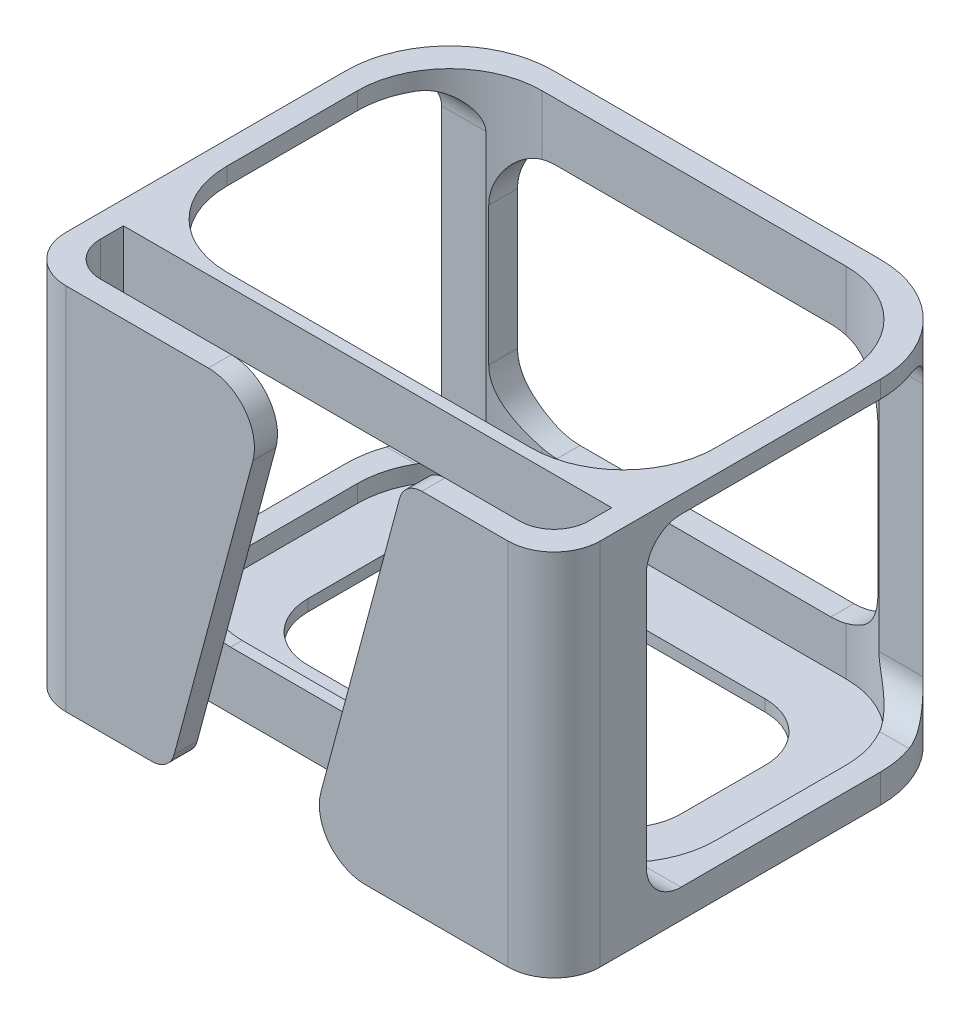
SolidWorks part; units mm, degrees
ref_plane "Front Plane" through (0, 0, 0) normal (0, 0, 1) x (1, 0, 0)
ref_plane "Top Plane" through (0, 0, 0) normal (0, 1, 0) x (1, 0, 0)
ref_plane "Right Plane" through (0, 0, 0) normal (1, 0, 0) x (0, 0, -1)
sketch "Sketch1" plane through (0, 0, 0) normal (0, 1, 0) x (1, 0, 0)
  line L0 (-0.3998, -21.65) -> (18.175, -21.65)
  line L1 (-14.175, 13.65) -> (12.175, 13.65)
  line L2 (-22.175, 5.65) -> (-22.175, -5.65)
  line L3 (-14.175, -13.65) -> (12.175, -13.65)
  line L4 (20.175, 5.65) -> (20.175, -5.65)
  line L5 (-22.175, -14.65) -> (20.175, -14.65)
  line L6 (-22.175, -14.65) -> (-22.175, -16.65)
  line L7 (-15.175, 15.65) -> (13.175, 15.65)
  line L8 (-24.175, 6.65) -> (-24.175, -8.65)
  line L10 (22.175, 6.65) -> (22.175, -8.65)
  line L11 (-19.175, -19.65) -> (-1.7581, -19.65)
  line L12 (20.175, -14.65) -> (20.175, -16.65)
  line L14 (-24.175, -8.65) -> (-24.175, -17.65)
  line L15 (-20.175, -21.65) -> (-1.7581, -21.65)
  line L16 (22.175, -8.65) -> (22.175, -17.65)
  line L18 (-1.7581, -21.65) -> (-1.7581, -19.65)
  line L20 (-0.3998, -21.65) -> (-0.3998, -19.65)
  line L23 (-0.3998, -19.65) -> (17.175, -19.65)
  arc A0 (12.175, 13.65) -> (20.175, 5.65) centre (12.175, 5.65) cw
  arc A1 (-22.175, -5.65) -> (-14.175, -13.65) centre (-14.175, -5.65) ccw
  arc A2 (-14.175, 13.65) -> (-22.175, 5.65) centre (-14.175, 5.65) ccw
  arc A3 (12.175, -13.65) -> (20.175, -5.65) centre (12.175, -5.65) ccw
  arc A6 (13.175, 15.65) -> (22.175, 6.65) centre (13.175, 6.65) cw
  arc A7 (-15.175, 15.65) -> (-24.175, 6.65) centre (-15.175, 6.65) ccw
  arc A8 (18.175, -21.65) -> (22.175, -17.65) centre (18.175, -17.65) ccw
  arc A9 (-24.175, -17.65) -> (-20.175, -21.65) centre (-20.175, -17.65) ccw
  arc A10 (17.175, -19.65) -> (20.175, -16.65) centre (17.175, -16.65) ccw
  arc A11 (-22.175, -16.65) -> (-19.175, -19.65) centre (-19.175, -16.65) ccw
  point P0 (0, 0)
  point P18 (0, 0)
  point P37 (-1, -21.65)
  dimension "D3" = 8
  dimension "D6" = 4
  dimension "D4" = 2
  dimension "D11" = 3
  dimension "D2" = 2
  dimension "D5" = 2
  dimension "D7" = 1
  dimension "D8" = 2
  dimension "D9" = 2
  dimension "D10" = 2
extrude "Boss-Extrude5" add sketch "Sketch1" along normal blind 32 contours A7 L8 L14 A9 L15 L18 L11 A11 L6 L5 L12 A10 L23 L20 L0 A8 L16 L10 A6 L7
sketch "Sketch6" plane through (0, 32, 0) normal (0, 1, 0) x (1, 0, 0)
  line L0 (-14.175, 13.65) -> (12.175, 13.65)
  line L1 (-22.175, 5.65) -> (-22.175, -5.65)
  line L2 (-14.175, -13.65) -> (12.175, -13.65)
  line L3 (20.175, 5.65) -> (20.175, -5.65)
  line L4 (-15.175, 15.65) -> (13.175, 15.65) construction
  line L5 (-24.175, 6.65) -> (-24.175, -17.65) construction
  line L6 (22.175, 6.65) -> (22.175, -17.65) construction
  line L7 (-22.175, -14.65) -> (20.175, -14.65) construction
  arc A0 (12.175, 13.65) -> (20.175, 5.65) centre (12.175, 5.65) cw
  arc A1 (-22.175, -5.65) -> (-14.175, -13.65) centre (-14.175, -5.65) ccw
  arc A2 (-14.175, 13.65) -> (-22.175, 5.65) centre (-14.175, 5.65) ccw
  arc A3 (12.175, -13.65) -> (20.175, -5.65) centre (12.175, -5.65) ccw
  dimension "D1" = 2
  dimension "D2" = 2
  dimension "D3" = 2
  dimension "D4" = 1
extrude "Cut-Extrude1" cut sketch "Sketch6" against normal blind 31
sketch "Sketch9" plane through (0, 1, 0) normal (0, 1, 0) x (1, 0, 0)
  line L0 (-22.175, 5.65) -> (-22.175, -5.65) construction
  line L1 (-12.175, 8.65) -> (10.175, 8.65)
  line L2 (-17.175, 3.65) -> (-17.175, -3.65)
  line L3 (-12.175, -8.65) -> (10.175, -8.65)
  line L4 (15.175, 3.65) -> (15.175, -3.65)
  line L5 (20.175, -5.65) -> (20.175, 5.65) construction
  line L6 (12.175, 13.65) -> (-14.175, 13.65) construction
  line L7 (-14.175, -13.65) -> (12.175, -13.65) construction
  arc A0 (10.175, 8.65) -> (15.175, 3.65) centre (10.175, 3.65) cw
  arc A1 (-17.175, -3.65) -> (-12.175, -8.65) centre (-12.175, -3.65) ccw
  arc A2 (10.175, -8.65) -> (15.175, -3.65) centre (10.175, -3.65) ccw
  arc A3 (-12.175, 8.65) -> (-17.175, 3.65) centre (-12.175, 3.65) ccw
  dimension "D5" = 5
  dimension "D1" = 5
  dimension "D2" = 5
  dimension "D3" = 5
  dimension "D4" = 5
extrude "Cut-Extrude2" cut sketch "Sketch9" against normal through all contours L1 A0 L4 A2 L3 A1 L2 A3
ref_plane "Plane7" through (0, 0, 34.65) normal (0, 0, 1) x (1, 0, 0)
sketch "Sketch11" plane through (0, 0, 34.65) normal (0, 0, 1) x (1, 0, 0)
  line L1 (-2.6006, 32) -> (-11.175, 0)
  line L2 (-20.175, 32) -> (-1.7581, 32) construction
  line L3 (-20.175, 0) -> (-1.7581, 0) construction
  line L4 (0.6006, 0) -> (9.175, 32)
  line L5 (-0.3998, 0) -> (18.175, 0) construction
  line L6 (-0.3998, 32) -> (18.175, 32) construction
  line L7 (-2.6006, 32) -> (9.175, 32)
  line L8 (-11.175, 0) -> (0.6006, 0)
  dimension "D1" = 75
  dimension "D2" = 9
  dimension "D3" = 9
extrude "Cut-Extrude3" cut sketch "Sketch11" against normal up to next
fillet "Fillet1" radius 4 2 edges at (0.6006, 0, 20.65) (-2.6006, 32, 20.65)
fillet "Fillet2" radius 2 2 edges at (9.175, 32, 20.65) (-11.175, 0, 20.65)
ref_plane "Plane10" through (-44.175, 0, 0) normal (-1, 0, 0) x (0, 0, 1)
sketch "Sketch13" plane through (-44.175, 0, 0) normal (-1, 0, 0) x (0, 0, 1)
  line L0 (-6.65, 32) -> (17.65, 32) construction
  line L1 (-9.65, 30.5) -> (10.65, 30.5)
  line L2 (-12.65, 27.5) -> (-12.65, 5.5)
  line L3 (-9.65, 2.5) -> (10.65, 2.5)
  line L4 (13.65, 27.5) -> (13.65, 5.5)
  line L5 (-5.65, 1) -> (-13.65, 1) construction
  line L6 (-13.65, 1) -> (-13.65, 32) construction
  line L7 (13.65, 1) -> (13.65, 32) construction
  arc A0 (10.65, 30.5) -> (13.65, 27.5) centre (10.65, 27.5) cw
  arc A1 (-12.65, 5.5) -> (-9.65, 2.5) centre (-9.65, 5.5) ccw
  arc A2 (10.65, 2.5) -> (13.65, 5.5) centre (10.65, 5.5) ccw
  arc A3 (-9.65, 30.5) -> (-12.65, 27.5) centre (-9.65, 27.5) ccw
  dimension "D5" = 3
  dimension "D1" = 1.5
  dimension "D2" = 1.5
  dimension "D3" = 1
  dimension "D4" = 0
extrude "Cut-Extrude4" cut sketch "Sketch13" against normal through all
ref_plane "Plane12" through (0, 0, -35.65) normal (0, 0, -1) x (-1, 0, 0)
sketch "Sketch14" plane through (0, 0, -35.65) normal (0, 0, -1) x (-1, 0, 0)
  line L0 (15.175, 32) -> (-13.175, 32) construction
  line L9 (-10.8832, 27) -> (12.8832, 27)
  line L10 (-15.8832, 22) -> (-15.8832, 10)
  line L11 (-10.8832, 5) -> (12.8832, 5)
  line L12 (17.8832, 22) -> (17.8832, 10)
  line L13 (15.175, 0) -> (-13.175, 0) construction
  line L14 (21.8832, 5.5) -> (21.8832, 27.5) construction
  line L15 (-19.8832, 5.5) -> (-19.8832, 27.5) construction
  arc A4 (12.8832, 27) -> (17.8832, 22) centre (12.8832, 22) cw
  arc A5 (-15.8832, 10) -> (-10.8832, 5) centre (-10.8832, 10) ccw
  arc A6 (12.8832, 5) -> (17.8832, 10) centre (12.8832, 10) ccw
  arc A7 (-10.8832, 27) -> (-15.8832, 22) centre (-10.8832, 22) ccw
  dimension "D5" = 5
  dimension "D1" = 5
  dimension "D2" = 5
  dimension "D3" = 4
  dimension "D4" = 4
extrude "Cut-Extrude5" cut sketch "Sketch14" against normal blind 55
